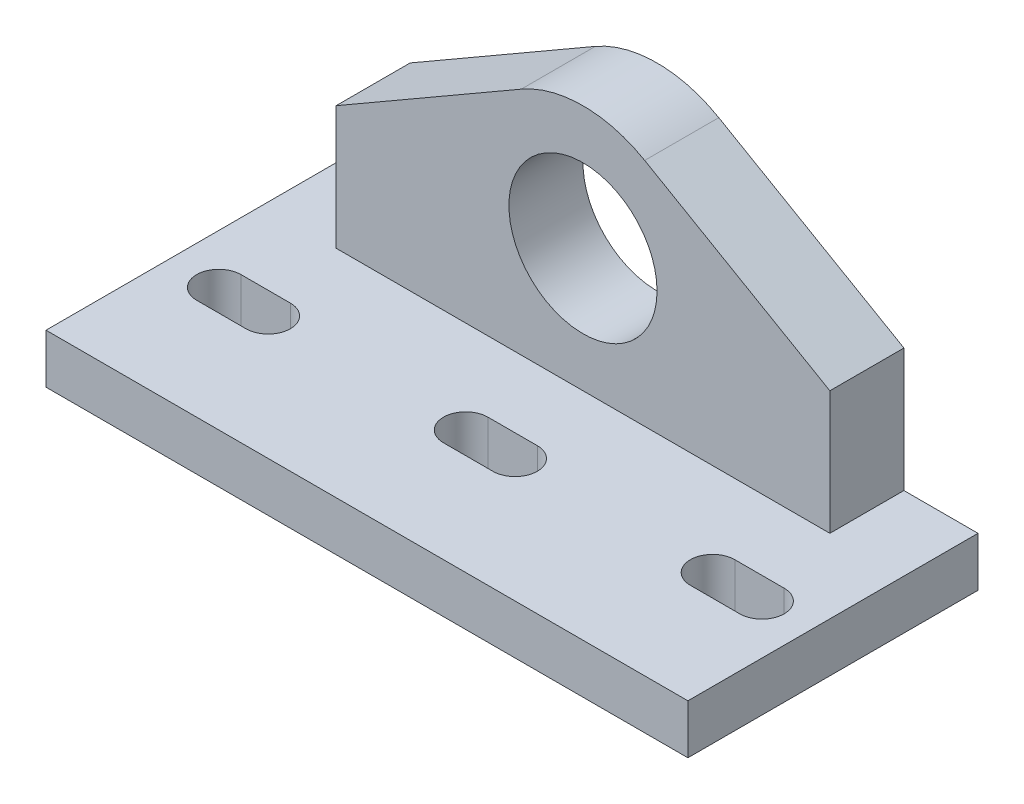
SolidWorks part; units mm, degrees
ref_plane "前视基准面" through (0, 0, 0) normal (0, 0, 1) x (1, 0, 0)
ref_plane "上视基准面" through (0, 0, 0) normal (0, 1, 0) x (1, 0, 0)
ref_plane "右视基准面" through (0, 0, 0) normal (1, 0, 0) x (0, 0, -1)
sketch "草图2" plane through (0, 0, 0) normal (0, 1, 0) x (1, 0, 0)
  line L1 (0, 0) -> (260, 0)
  line L2 (0, 0) -> (0, -117.5)
  line L3 (0, -117.5) -> (260, -117.5)
  line L4 (260, 0) -> (260, -117.5)
  dimension "D1" = 260
  dimension "D2" = 117.5
extrude "凸台-拉伸1" add sketch "草图2" along normal blind 20
sketch "草图3" plane through (0, 20, 0) normal (0, 1, 0) x (1, 0, 0)
  line L0 (20, -67.5) -> (40, -67.5) construction
  line L1 (20, -58.5) -> (40, -58.5)
  line L2 (20, -76.5) -> (40, -76.5)
  line L3 (260, 0) -> (0, 0) construction
  line L4 (130, 0) -> (130, -117.5) construction
  line L5 (0, -117.5) -> (260, -117.5) construction
  arc A0 (20, -58.5) -> (20, -76.5) centre (20, -67.5) ccw
  arc A1 (40, -76.5) -> (40, -58.5) centre (40, -67.5) ccw
  point P2 (30, -67.5)
  dimension "D1" = 20
  dimension "D2" = 18
  dimension "D3" = 67.5
  dimension "D4" = 100
extrude "切除-拉伸1" cut sketch "草图3" against normal through all
pattern_linear "阵列(线性)1" count 3 spacing 100 along (1, 0, 0) of "切除-拉伸1"
sketch "草图4" plane through (0, 20, 0) normal (0, 1, 0) x (1, 0, 0)
  line L0 (260, 0) -> (0, 0) construction
  line L1 (30, 0) -> (230, 0)
  line L2 (30, 0) -> (30, -30)
  line L3 (30, -30) -> (230, -30)
  line L4 (230, 0) -> (230, -30)
  line L5 (130, 0) -> (130, -117.5) construction
  line L6 (0, -117.5) -> (260, -117.5) construction
  point P10 (130, 0)
  dimension "D1" = 200
  dimension "D2" = 30
extrude "凸台-拉伸2" add sketch "草图4" along normal blind 100
sketch "草图5" plane through (0, 0, 30) normal (0, 0, 1) x (1, 0, 0)
  line L0 (130, 0) -> (130, 120) construction
  line L1 (0, 0) -> (260, 0) construction
  line L2 (30, 120) -> (230, 120) construction
  line L3 (30, 70) -> (105, 113.3013)
  line L4 (30, 120) -> (30, 20) construction
  line L5 (230, 70) -> (155, 113.3013)
  line L6 (230, 120) -> (230, 20) construction
  line L7 (30, 70) -> (30, 137.2991)
  line L8 (30, 137.2991) -> (230, 137.2991)
  line L9 (230, 137.2991) -> (230, 70)
  circle A0 centre (130, 70) radius 30
  arc A1 (105, 113.3013) -> (155, 113.3013) centre (130, 70) cw
  dimension "D1" = 70
  dimension "D2" = 60
  dimension "D3" = 50
extrude "切除-拉伸2" cut sketch "草图5" against normal through all
